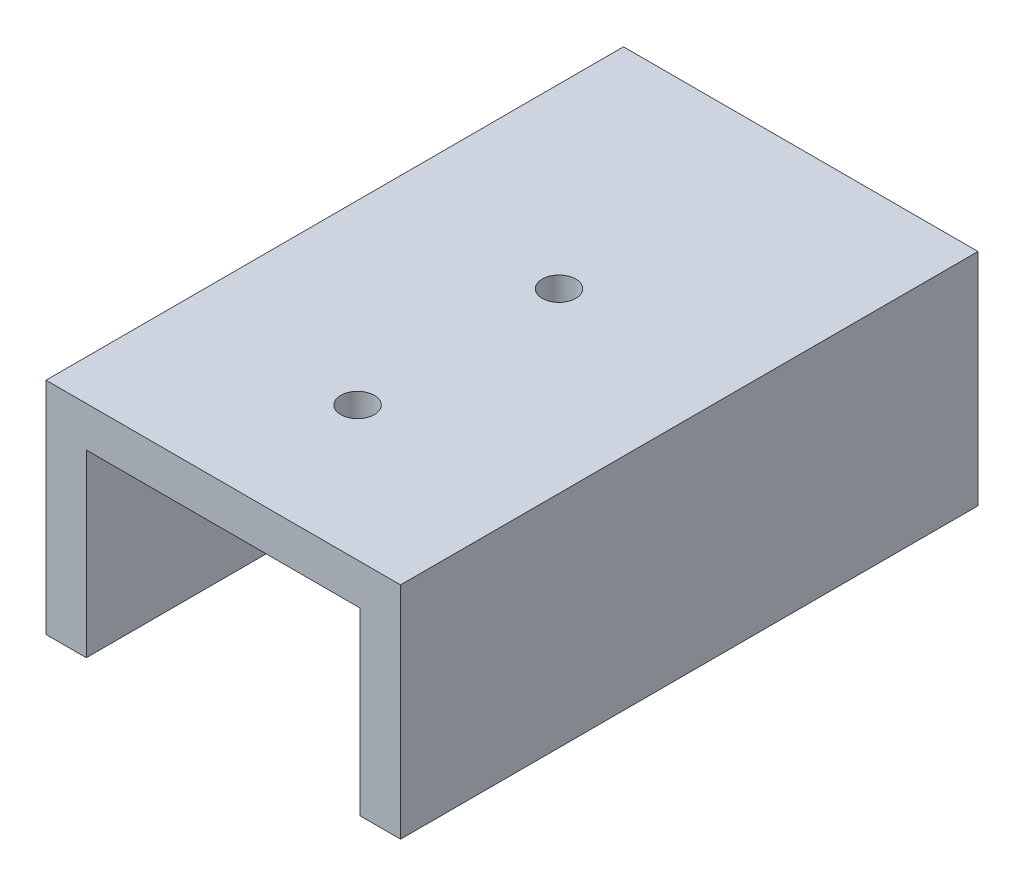
SolidWorks part; units mm, degrees
ref_plane "Front Plane" through (0, 0, 0) normal (0, 0, 1) x (1, 0, 0)
ref_plane "Top Plane" through (0, 0, 0) normal (0, 1, 0) x (1, 0, 0)
ref_plane "Right Plane" through (0, 0, 0) normal (1, 0, 0) x (0, 0, -1)
sketch "Sketch1" plane through (0, 0, 0) normal (0, 0, 1) x (1, 0, 0)
  line L1 (-10.2, 10.2) -> (10.2, 10.2)
  line L2 (-10.2, 10.2) -> (-10.2, -10.2)
  line L3 (-10.2, -10.2) -> (10.2, -10.2)
  line L4 (10.2, 10.2) -> (10.2, -10.2)
  line L5 (-10.2, 10.2) -> (10.2, -10.2) construction
  line L6 (-10.2, -10.2) -> (10.2, 10.2) construction
  line L7 (-13.2, 13.2) -> (13.2, 13.2)
  line L8 (-13.2, 13.2) -> (-13.2, -13.2)
  line L9 (-13.2, -13.2) -> (13.2, -13.2)
  line L10 (13.2, 13.2) -> (13.2, -13.2)
  line L11 (-13.2, 13.2) -> (13.2, -13.2) construction
  line L12 (-13.2, -13.2) -> (13.2, 13.2) construction
  point P0 (0, 0)
  point P6 (0, 0)
  dimension "D1" = 20.4
  dimension "D2" = 20.4
  dimension "D3" = 26.4
  dimension "D4" = 26.4
extrude "Boss-Extrude1" add sketch "Sketch1" along normal blind 40
sketch "Sketch2" plane through (0, 0, 0) normal (0, 0, -1) x (-1, 0, 0)
  line L1 (-13.2, 13.2) -> (13.2, 13.2)
  line L2 (-13.2, 13.2) -> (-13.2, -13.2)
  line L3 (-13.2, -13.2) -> (13.2, -13.2)
  line L4 (13.2, 13.2) -> (13.2, -13.2)
extrude "Boss-Extrude2" add sketch "Sketch2" along normal blind 3
sketch "Sketch3" plane through (0, -13.2, 0) normal (0, -1, 0) x (1, 0, 0)
  line L4 (-10.2, 0) -> (10.2, 0)
  line L5 (-10.2, 40) -> (-10.2, 0)
  line L6 (10.2, 40) -> (-10.2, 40)
  line L7 (10.2, 0) -> (10.2, 40)
  line L8 (-10.2, 0) -> (10.2, 0)
  line L9 (-10.2, 40) -> (-10.2, 0)
  line L10 (10.2, 40) -> (-10.2, 40)
  line L11 (10.2, 0) -> (10.2, 40)
  dimension "D1" = 0
extrude "Cut-Extrude1" cut sketch "Sketch3" against normal blind 3
sketch "Sketch4" plane through (0, 13.2, 0) normal (0, 1, 0) x (1, 0, 0)
  line L0 (10.2, 0) -> (-10.2, 0) construction
  line L1 (10.2, 0) -> (-10.2, 0)
  line L2 (13.2, -40) -> (13.2, 3) construction
  circle A0 centre (0, -15) radius 1.25
  circle A1 centre (0, -30) radius 1.25
  text T0 "<b>V</b>"
  dimension "D3" = 2.5
  dimension "D4" = 2.5
  dimension "D1" = 15
  dimension "D2" = 30
  dimension "D5" = 13.2
  dimension "D6" = 13.2
extrude "Cut-Extrude2" cut sketch "Sketch4" against normal blind 3 contours A0 | A1
sketch "Sketch5" plane through (0, -13.2, 0) normal (0, -1, 0) x (1, 0, 0)
  line L1 (13.2, -3) -> (-13.2, -3)
  line L2 (13.2, -3) -> (13.2, 40)
  line L3 (13.2, 40) -> (-13.2, 40)
  line L4 (-13.2, -3) -> (-13.2, 40)
extrude "Cut-Extrude3" cut sketch "Sketch5" against normal blind 10
